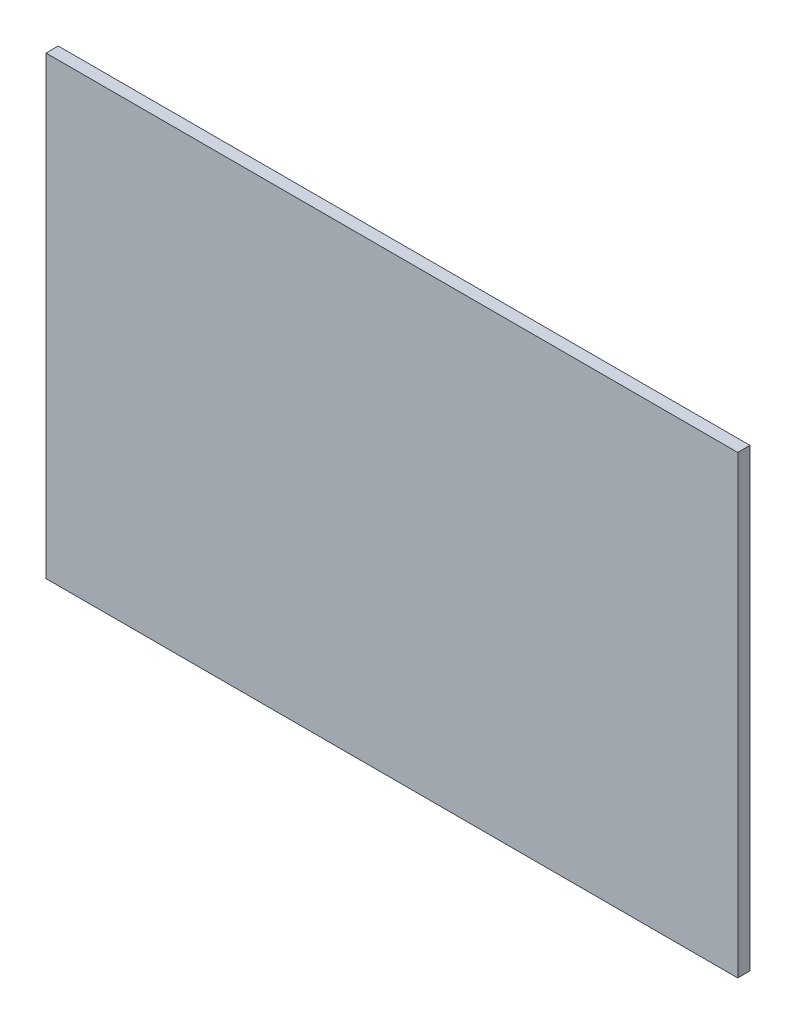
SolidWorks part; units mm, degrees
ref_plane "Front Plane" through (0, 0, 0) normal (0, 0, 1) x (1, 0, 0)
ref_plane "Top Plane" through (0, 0, 0) normal (0, 1, 0) x (1, 0, 0)
ref_plane "Right Plane" through (0, 0, 0) normal (1, 0, 0) x (0, 0, -1)
sketch "Sketch1" plane through (0, 0, 0) normal (0, 0, 1) x (1, 0, 0)
  line L1 (-20, 25.8895) -> (150, 25.8895)
  line L2 (-20, 25.8895) -> (-20, -85.9788)
  line L3 (-20, -85.9788) -> (150, -85.9788)
  line L4 (150, 25.8895) -> (150, -85.9788)
  dimension "D1" = 0
extrude "Boss-Extrude1" add sketch "Sketch1" along normal blind 3
